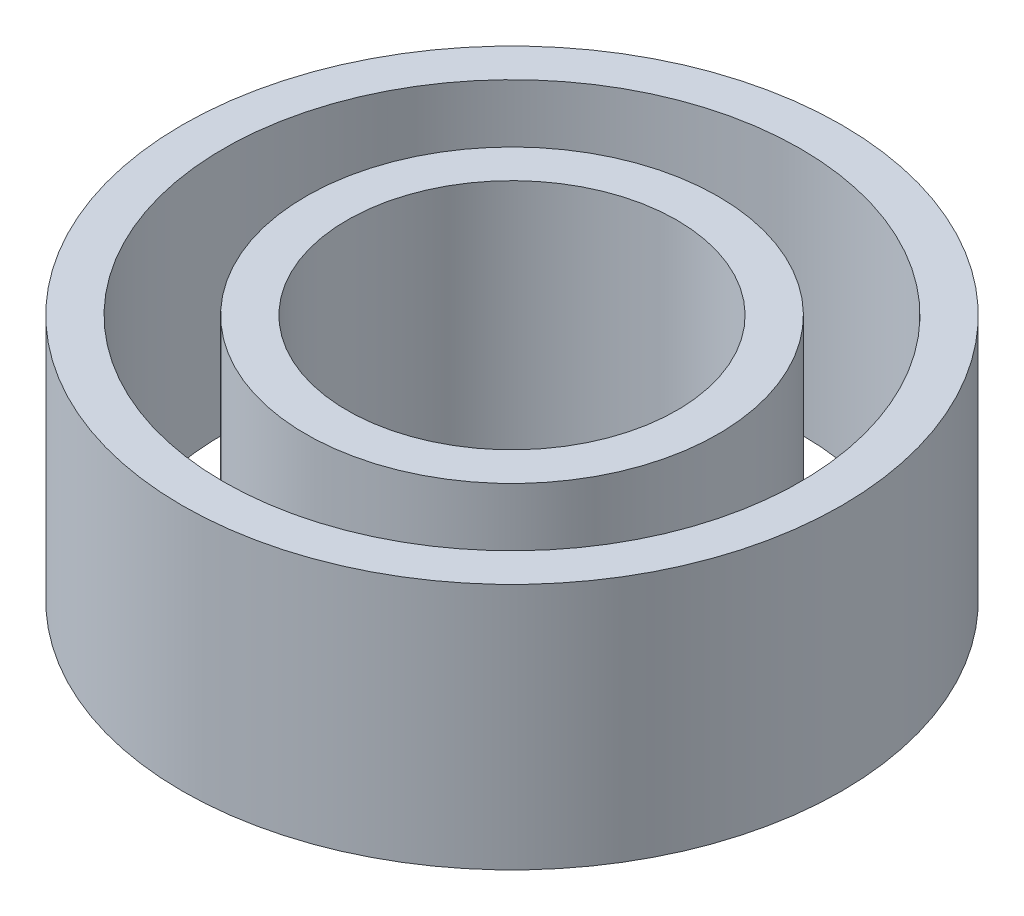
SolidWorks part; units mm, degrees
ref_plane "Plan de face" through (0, 0, 0) normal (0, 0, 1) x (1, 0, 0)
ref_plane "Plan de dessus" through (0, 0, 0) normal (0, 1, 0) x (1, 0, 0)
ref_plane "Plan de droite" through (0, 0, 0) normal (1, 0, 0) x (0, 0, -1)
sketch "Esquisse1" plane through (0, 0, 0) normal (0, 0, 1) x (1, 0, 0)
  line L0 (0, 0) -> (0, 4.6087) construction
  line L1 (2, 1) -> (2.5, 1)
  line L2 (2, 1) -> (2, 4)
  line L3 (2, 4) -> (2.5, 4)
  line L4 (2.5, 1) -> (2.5, 4)
  line L5 (3.5, 1) -> (4, 1)
  line L6 (3.5, 1) -> (3.5, 4)
  line L7 (3.5, 4) -> (4, 4)
  line L8 (4, 1) -> (4, 4)
  dimension "D1" = 2
  dimension "D2" = 3
  dimension "D3" = 3
  dimension "D4" = 4
  dimension "D5" = 0.5
  dimension "D6" = 0.5
revolve "Révolution1" add sketch "Esquisse1" angle 360 about L0
